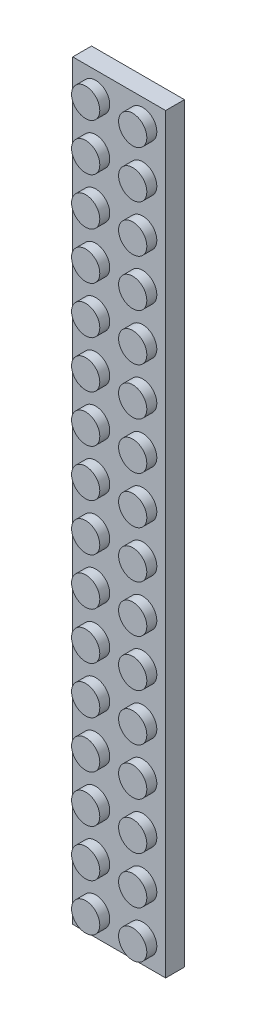
SolidWorks part; units mm, degrees
ref_plane "Спереди" through (0, 0, 0) normal (0, 0, 1) x (1, 0, 0)
ref_plane "Сверху" through (0, 0, 0) normal (0, 1, 0) x (1, 0, 0)
ref_plane "Справа" through (0, 0, 0) normal (1, 0, 0) x (0, 0, -1)
sketch "Эскиз1" plane through (0, 0, 0) normal (0, 0, 1) x (1, 0, 0)
  line L1 (-7.9, -63.9) -> (7.9, -63.9)
  line L2 (-7.9, -63.9) -> (-7.9, 63.9)
  line L3 (-7.9, 63.9) -> (7.9, 63.9)
  line L4 (7.9, -63.9) -> (7.9, 63.9)
  line L5 (-7.9, -63.9) -> (7.9, 63.9) construction
  line L6 (-7.9, 63.9) -> (7.9, -63.9) construction
  point P0 (0, 0)
  dimension "D1" = 15.8
  dimension "D2" = 127.8
extrude "Бобышка-Вытянуть1" add sketch "Эскиз1" along normal blind 3.2
sketch "Эскиз2" plane through (0, 0, 3.2) normal (0, 0, 1) x (1, 0, 0)
  line L0 (-7.9, 63.9) -> (-7.9, -63.9) construction
  line L1 (7.9, 63.9) -> (-7.9, 63.9) construction
  circle A0 centre (-4, 60) radius 2.4
  circle A1 centre (4, 60) radius 2.4
  circle A2 centre (4, 52) radius 2.4
  circle A3 centre (4, 44) radius 2.4
  circle A4 centre (4, 36) radius 2.4
  circle A5 centre (4, 28) radius 2.4
  circle A6 centre (4, 20) radius 2.4
  circle A7 centre (4, 12) radius 2.4
  circle A8 centre (4, 4) radius 2.4
  circle A9 centre (4, -4) radius 2.4
  circle A10 centre (4, -12) radius 2.4
  circle A11 centre (4, -20) radius 2.4
  circle A12 centre (4, -28) radius 2.4
  circle A13 centre (4, -36) radius 2.4
  circle A14 centre (4, -44) radius 2.4
  circle A15 centre (4, -52) radius 2.4
  circle A16 centre (4, -60) radius 2.4
  circle A17 centre (-4, 52) radius 2.4
  circle A18 centre (-4, 44) radius 2.4
  circle A19 centre (-4, 36) radius 2.4
  circle A20 centre (-4, 28) radius 2.4
  circle A21 centre (-4, 20) radius 2.4
  circle A22 centre (-4, 12) radius 2.4
  circle A23 centre (-4, 4) radius 2.4
  circle A24 centre (-4, -4) radius 2.4
  circle A25 centre (-4, -12) radius 2.4
  circle A26 centre (-4, -20) radius 2.4
  circle A27 centre (-4, -28) radius 2.4
  circle A28 centre (-4, -36) radius 2.4
  circle A29 centre (-4, -44) radius 2.4
  circle A30 centre (-4, -52) radius 2.4
  circle A31 centre (-4, -60) radius 2.4
  dimension "D1" = 3.9
  dimension "D2" = 3.9
  dimension "D3" = 2
  dimension "D4" = 16
extrude "Бобышка-Вытянуть2" add sketch "Эскиз2" along normal blind 1.7
sketch "Эскиз3" plane through (0, 0, 0) normal (0, 0, -1) x (-1, 0, 0)
  line L0 (-7.9, -63.9) -> (-7.9, 63.9) construction
  line L1 (-7.9, 63.9) -> (7.9, 63.9) construction
  circle A0 centre (-4, 60) radius 2.5
  circle A1 centre (4, 60) radius 2.5
  circle A2 centre (4, 52) radius 2.5
  circle A3 centre (4, 44) radius 2.5
  circle A4 centre (4, 36) radius 2.5
  circle A5 centre (4, 28) radius 2.5
  circle A6 centre (4, 20) radius 2.5
  circle A7 centre (4, 12) radius 2.5
  circle A8 centre (4, 4) radius 2.5
  circle A9 centre (4, -4) radius 2.5
  circle A10 centre (4, -12) radius 2.5
  circle A11 centre (4, -20) radius 2.5
  circle A12 centre (4, -28) radius 2.5
  circle A13 centre (4, -36) radius 2.5
  circle A14 centre (4, -44) radius 2.5
  circle A15 centre (4, -52) radius 2.5
  circle A16 centre (4, -60) radius 2.5
  circle A17 centre (-4, 52) radius 2.5
  circle A18 centre (-4, 44) radius 2.5
  circle A19 centre (-4, 36) radius 2.5
  circle A20 centre (-4, 28) radius 2.5
  circle A21 centre (-4, 20) radius 2.5
  circle A22 centre (-4, 12) radius 2.5
  circle A23 centre (-4, 4) radius 2.5
  circle A24 centre (-4, -4) radius 2.5
  circle A25 centre (-4, -12) radius 2.5
  circle A26 centre (-4, -20) radius 2.5
  circle A27 centre (-4, -28) radius 2.5
  circle A28 centre (-4, -36) radius 2.5
  circle A29 centre (-4, -44) radius 2.5
  circle A30 centre (-4, -52) radius 2.5
  circle A31 centre (-4, -60) radius 2.5
  dimension "D1" = 3.9
  dimension "D2" = 3.9
  dimension "D3" = 2
  dimension "D4" = 16
extrude "Вырез-Вытянуть1" cut sketch "Эскиз3" against normal blind 1.8
